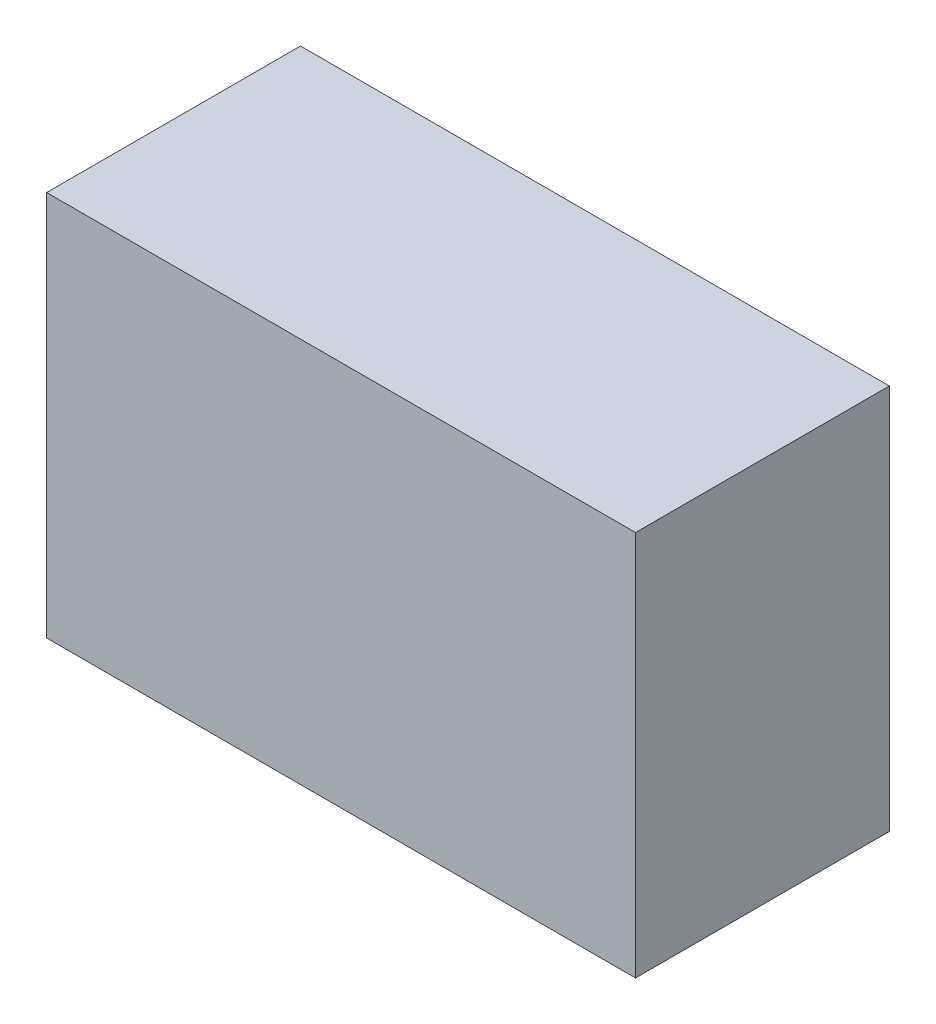
SolidWorks part; units mm, degrees
ref_plane "Front Plane" through (0, 0, 0) normal (0, 0, 1) x (1, 0, 0)
ref_plane "Top Plane" through (0, 0, 0) normal (0, 1, 0) x (1, 0, 0)
ref_plane "Right Plane" through (0, 0, 0) normal (1, 0, 0) x (0, 0, -1)
sketch "Sketch1" plane through (0, 0, 0) normal (0, 0, 1) x (1, 0, 0)
  line L1 (1.45, 0.95) -> (-1.45, 0.95)
  line L2 (1.45, 0.95) -> (1.45, -0.95)
  line L3 (1.45, -0.95) -> (-1.45, -0.95)
  line L4 (-1.45, 0.95) -> (-1.45, -0.95)
  line L5 (1.45, 0.95) -> (-1.45, -0.95) construction
  line L6 (1.45, -0.95) -> (-1.45, 0.95) construction
  point P0 (0, 0)
  dimension "D1" = 1.9
  dimension "D2" = 2.9
extrude "Boss-Extrude1" add sketch "Sketch1" along normal blind 1.25
